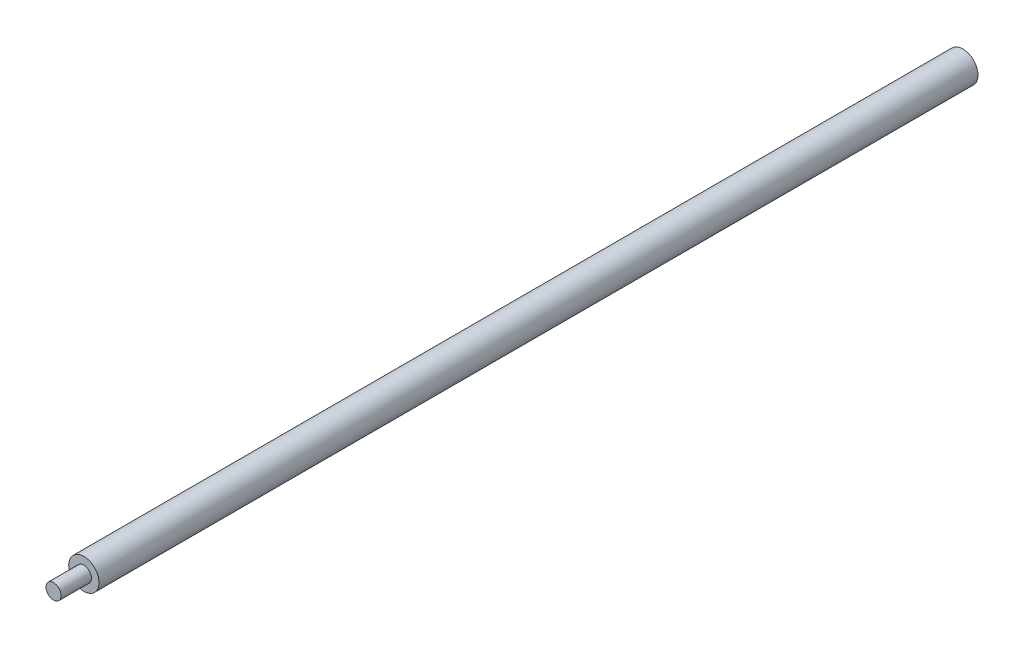
SolidWorks part; units mm, degrees
ref_plane "Front Plane" through (0, 0, 0) normal (0, 0, 1) x (1, 0, 0)
ref_plane "Top Plane" through (0, 0, 0) normal (0, 1, 0) x (1, 0, 0)
ref_plane "Right Plane" through (0, 0, 0) normal (1, 0, 0) x (0, 0, -1)
sketch "Sketch1" plane through (0, 0, 0) normal (0, 0, 1) x (1, 0, 0)
  circle A1 centre (0, 0) radius 2.5
  dimension "D2" = 5
extrude "Boss-Extrude1" add sketch "Sketch1" along normal blind 145
sketch "Sketch2" plane through (0, 0, 145) normal (0, 0, 1) x (1, 0, 0)
  circle A0 centre (0, 0) radius 1.25
  dimension "D1" = 2.5
extrude "Boss-Extrude2" add sketch "Sketch2" along normal blind 5
sketch "Sketch3" plane through (0, 0, 0) normal (0, 0, -1) x (-1, 0, 0)
  circle A0 centre (0, 0) radius 1.25
  dimension "D1" = 2.5
extrude "Cut-Extrude1" cut sketch "Sketch3" against normal blind 5
